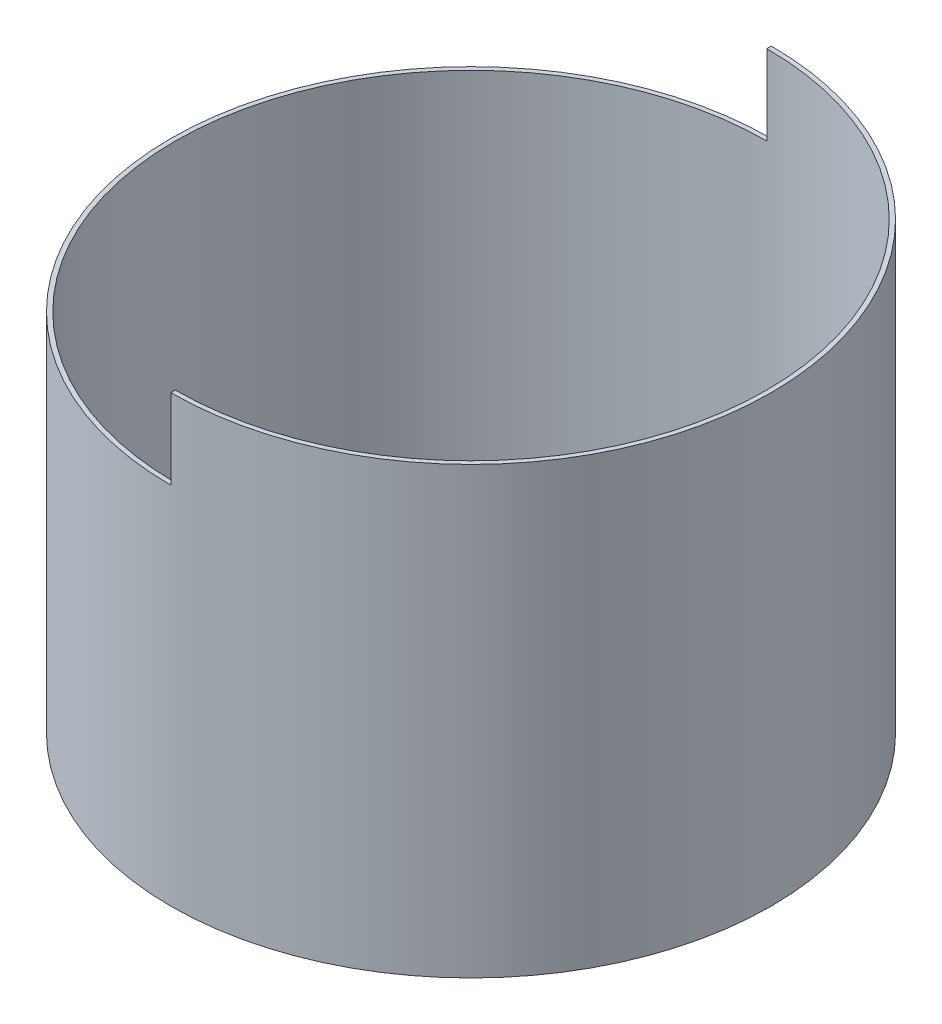
SolidWorks part; units mm, degrees
ref_plane "前视基准面" through (0, 0, 0) normal (0, 0, 1) x (1, 0, 0)
ref_plane "上视基准面" through (0, 0, 0) normal (0, 1, 0) x (1, 0, 0)
ref_plane "右视基准面" through (0, 0, 0) normal (1, 0, 0) x (0, 0, -1)
sketch "草图1" plane through (0, 0, 0) normal (0, 1, 0) x (1, 0, 0)
  circle A0 centre (0, 0) radius 67.5
  circle A1 centre (0, 0) radius 66.5
  dimension "D1" = 1
  dimension "D2" = 135
extrude "凸台-拉伸1" add sketch "草图1" along normal blind 100
sketch "草图2" plane through (0, 100, 0) normal (0, 1, 0) x (1, 0, 0)
  line L1 (-67.5, -67.5) -> (0, -67.5)
  line L2 (-67.5, -67.5) -> (-67.5, 67.5)
  line L3 (-67.5, 67.5) -> (0, 67.5)
  line L4 (0, -67.5) -> (0, 67.5)
  line L5 (-67.5, -67.5) -> (0, 67.5) construction
  line L6 (-67.5, 67.5) -> (0, -67.5) construction
  circle A0 centre (0, 0) radius 67.5 construction
  point P0 (-33.75, 0)
extrude "切除-拉伸1" cut sketch "草图2" against normal blind 18
